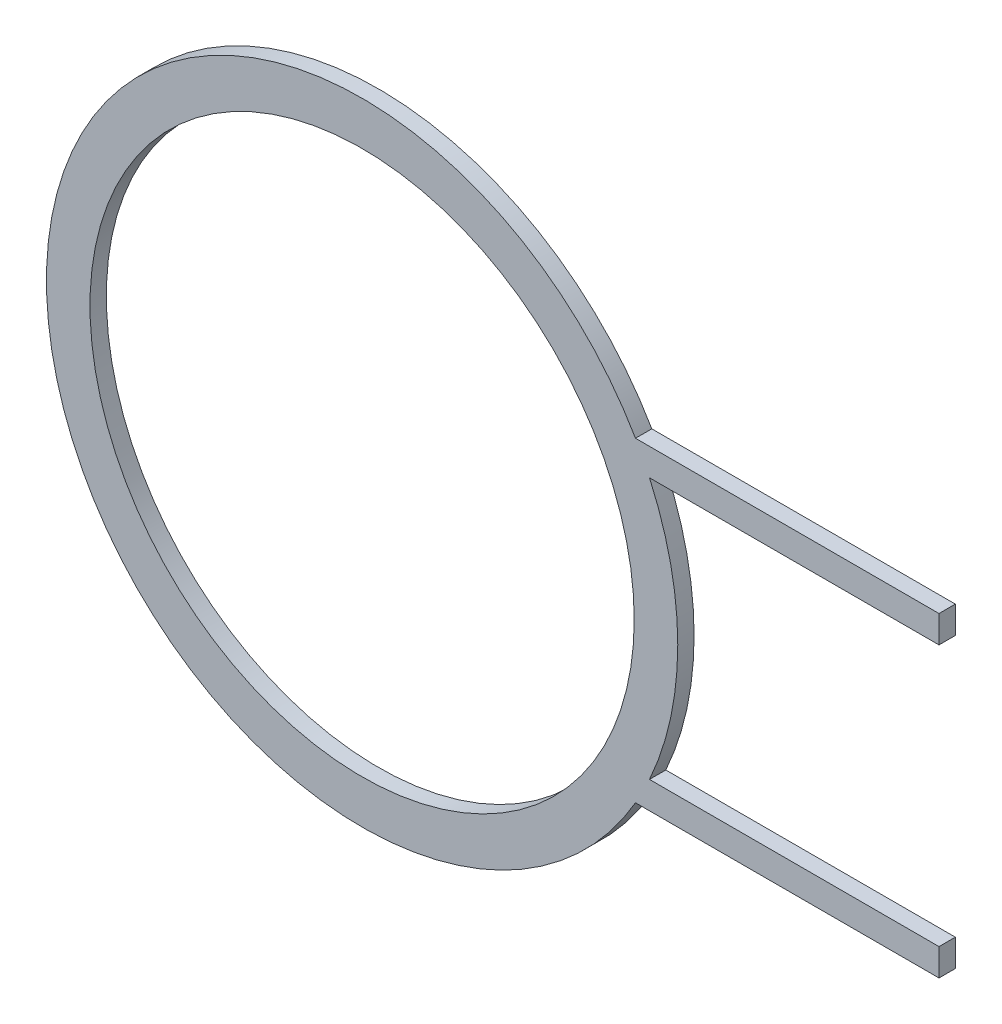
SolidWorks part; units mm, degrees
ref_plane "前基準面" through (0, 0, 0) normal (0, 0, 1) x (1, 0, 0)
ref_plane "上基準面" through (0, 0, 0) normal (0, 1, 0) x (1, 0, 0)
ref_plane "右基準面" through (0, 0, 0) normal (1, 0, 0) x (0, 0, -1)
sketch "草圖1" plane through (0, 0, 0) normal (0, 0, 1) x (1, 0, 0)
  line L0 (0, 0) -> (58, 0) construction
  line L1 (106, 24) -> (52.8015, 24)
  line L2 (106, -24) -> (106, -29)
  line L3 (106, 24) -> (106, 29)
  line L4 (106, 29) -> (50.2295, 29)
  line L5 (106, -29) -> (50.2295, -29)
  line L6 (106, -24) -> (52.8015, -24)
  arc A1 (50.2295, 29) -> (50.2295, -29) centre (0, 0) ccw
  arc A2 (52.8015, -24) -> (52.8015, 24) centre (0, 0) ccw
  dimension "D1" = 116
  dimension "D2" = 24
  dimension "D3" = 5
extrude "填料-伸長1" add sketch "草圖1" along normal blind 3 contours L4 A1 L5 L2 L6 A2 L1 L3
sketch "草圖5" plane through (0, 0, 3) normal (0, 0, 1) x (1, 0, 0)
  circle A0 centre (0, 0) radius 50
  dimension "D1" = 100
extrude "除料-伸長1" cut sketch "草圖5" against normal blind 3 contours A0
